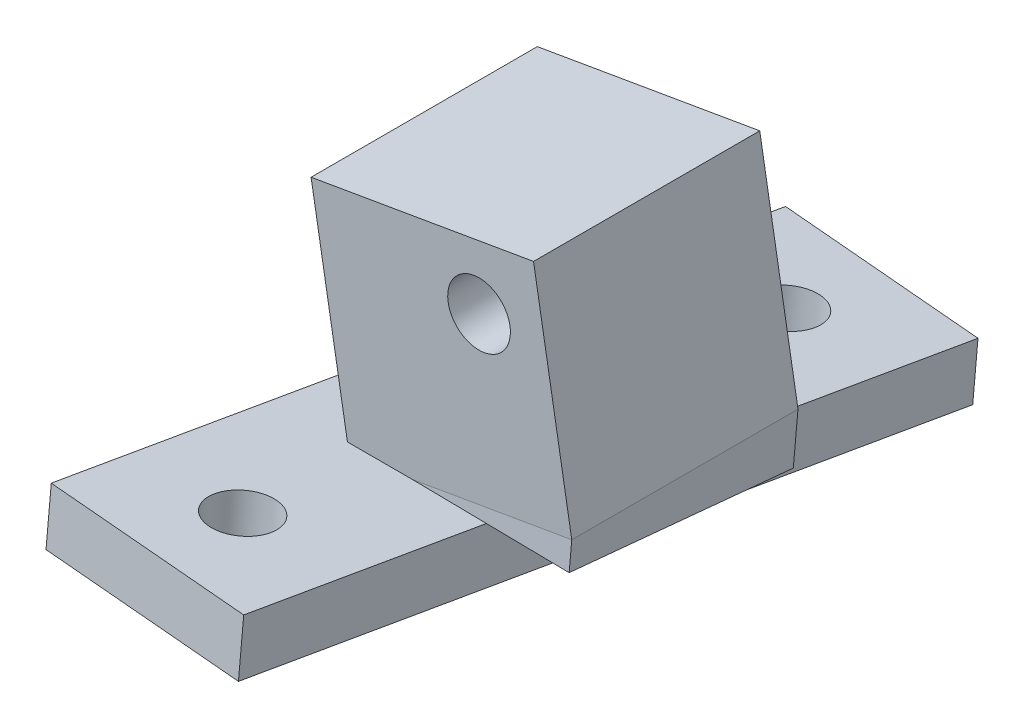
SolidWorks part; units mm, degrees
ref_plane "Front Plane" through (0, 0, 0) normal (0, 0, 1) x (1, 0, 0)
ref_plane "Top Plane" through (0, 0, 0) normal (0, 1, 0) x (1, 0, 0)
ref_plane "Right Plane" through (0, 0, 0) normal (1, 0, 0) x (0, 0, -1)
sketch "Sketch1" plane through (0, 0, 0) normal (0, 0, 1) x (1, 0, 0)
  line L0 (-279.481, 265.179) -> (-302.0094, 261.2995)
  line L1 (-302.0094, 261.2995) -> (-298.1384, 238.8202)
  line L2 (-298.1384, 238.8202) -> (-275.61, 242.6997)
  line L3 (-275.61, 242.6997) -> (-279.481, 265.179)
  circle A0 centre (-285, 257.8082) radius 3.175
  dimension "D2" = 6.35
  dimension "D1" = 3.81
  dimension "D3" = 3.81
  dimension "D4" = 22.8102
  dimension "D5" = 22.86
extrude "Boss-Extrude1" add sketch "Sketch1" along normal up to surface (22.9108 mm away)
ref_plane "Plane1" through (0, 235.5556, -22.5888) normal (0, 0.9954, -0.0955) x (1, 0, 0)
sketch "Sketch2" plane through (0, 235.5556, -22.5888) normal (0, 0.9954, -0.0955) x (1, 0, 0)
  line L0 (-301.3408, 1.8926) -> (-307.7396, -66.3883)
  line L1 (-307.7396, -66.3883) -> (-286.2438, -68.4027)
  line L2 (-286.2438, -68.4027) -> (-279.845, -0.1219)
  line L3 (-301.3408, 1.8926) -> (-279.845, -0.1219)
  line L4 (-298.1384, -22.7972) -> (-275.61, -23.1676) construction
  circle A0 centre (-291.4224, -7.9659) radius 3.175
  circle A1 centre (-296.1622, -58.5443) radius 3.175
  dimension "D5" = 10.795
  dimension "D9" = 6.35
  dimension "D10" = 6.35
  dimension "D1" = 21.59
  dimension "D2" = 68.58
  dimension "D3" = 7.62
  dimension "D4" = 21.59
  dimension "D6" = 8.89
  dimension "D7" = 8.89
  dimension "D8" = 10.795
  dimension "D11" = 94.412
extrude "Boss-Extrude2" add sketch "Sketch2" against normal blind 5.588
sketch "Sketch4" plane through (0, 235.5556, -22.5888) normal (0, 0.9954, -0.0955) x (1, 0, 0)
  line L0 (-284.1288, -45.8337) -> (-281.9948, -23.0626)
  line L4 (-279.845, -0.1219) -> (-301.3408, 1.8926)
  line L5 (-301.3408, 1.8926) -> (-307.7396, -66.3883)
  line L6 (-307.7396, -66.3883) -> (-286.2438, -68.4027)
  line L7 (-286.2438, -68.4027) -> (-279.845, -0.1219)
  line L8 (-279.845, -0.1219) -> (-301.3408, 1.8926)
  line L9 (-301.3408, 1.8926) -> (-307.7396, -66.3883)
  line L10 (-307.7396, -66.3883) -> (-286.2438, -68.4027)
  line L11 (-286.2438, -68.4027) -> (-279.845, -0.1219)
  line L13 (-291.7591, -45.7083) -> (-275.61, -45.9737)
  line L14 (-298.1384, -34.2003) -> (-291.7591, -45.7083)
  line L15 (-298.1384, -22.7972) -> (-298.1384, -34.2003)
  line L16 (-275.61, -23.1676) -> (-298.1384, -22.7972)
  line L17 (-275.61, -45.9737) -> (-275.61, -23.1676)
  line L18 (-291.7591, -45.7083) -> (-275.61, -45.9737)
  line L19 (-298.1384, -34.2003) -> (-291.7591, -45.7083)
  line L20 (-298.1384, -22.7972) -> (-298.1384, -34.2003)
  line L21 (-275.61, -23.1676) -> (-298.1384, -22.7972)
  line L22 (-275.61, -45.9737) -> (-275.61, -23.1676)
  line M13 (-286.2438, -68.4027) -> (-279.845, -0.1219)
  line M17 (-298.1384, -34.2003) -> (-291.7591, -45.7083)
  dimension "D1" = 0
  dimension "D2" = 0
extrude "Boss-Extrude3" add sketch "Sketch4" along normal up to surface contours L21 L20 L18 M13 M17 up to face at (-287.8512, 240.5917, 11.4554)
